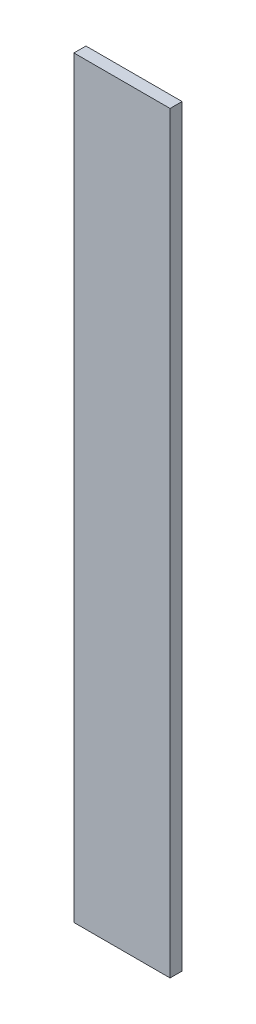
SolidWorks part; units mm, degrees
ref_plane "前视基准面" through (0, 0, 0) normal (0, 0, 1) x (1, 0, 0)
ref_plane "上视基准面" through (0, 0, 0) normal (0, 1, 0) x (1, 0, 0)
ref_plane "右视基准面" through (0, 0, 0) normal (1, 0, 0) x (0, 0, -1)
other "Configuration Table"
sketch "草图1" plane through (0, 0, 0) normal (0, 0, 1) x (1, 0, 0)
  line L0 (0, 0) -> (24, 0)
  line L1 (24, 0) -> (24, 188)
  line L2 (24, 188) -> (0, 188)
  line L3 (0, 188) -> (0, 0)
  dimension "width" = 24
  dimension "height" = 188
extrude "BlockExtrude" add sketch "草图1" along normal blind 3
